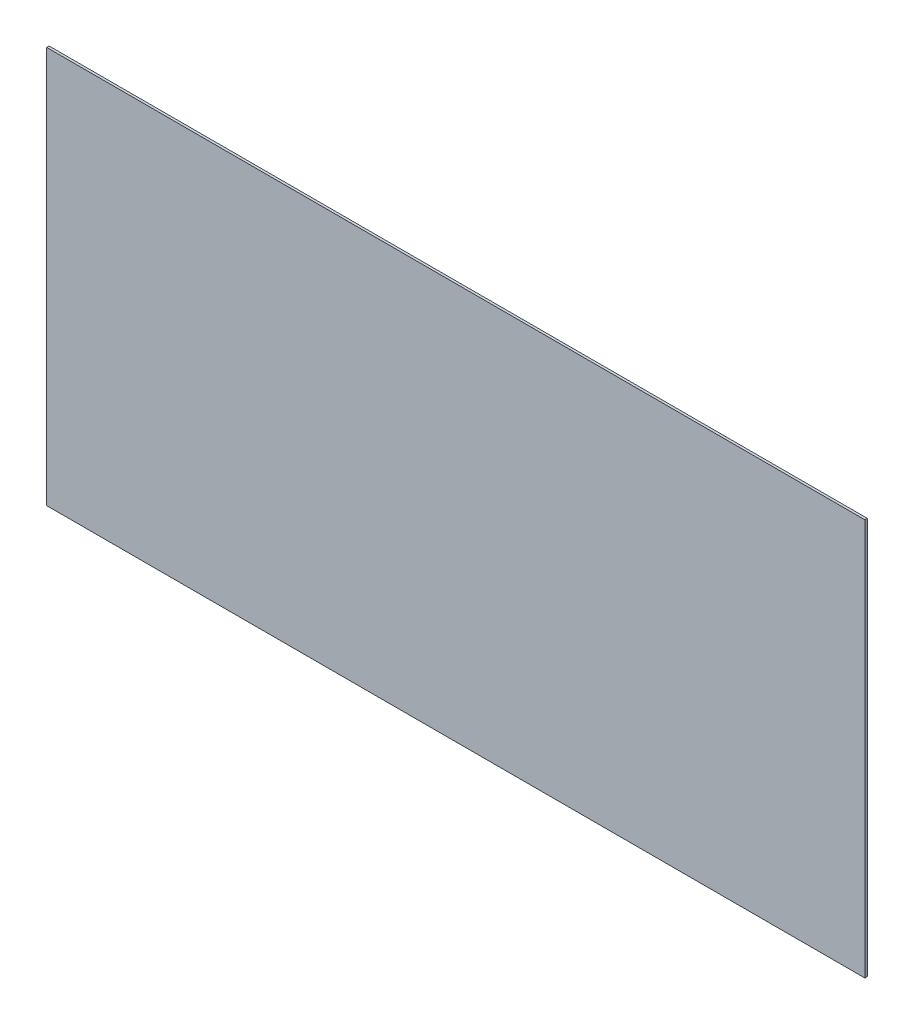
SolidWorks part; units mm, degrees
ref_plane "Plano frontal" through (0, 0, 0) normal (0, 0, 1) x (1, 0, 0)
ref_plane "Plano superior" through (0, 0, 0) normal (0, 1, 0) x (1, 0, 0)
ref_plane "Plano direito" through (0, 0, 0) normal (1, 0, 0) x (0, 0, -1)
sketch "Esboço1" plane through (0, 0, 0) normal (0, 0, 1) x (1, 0, 0)
  line L1 (-25.512, 6.0591) -> (41.488, 6.0591)
  line L2 (-25.512, 6.0591) -> (-25.512, -26.4409)
  line L3 (-25.512, -26.4409) -> (41.488, -26.4409)
  line L4 (41.488, 6.0591) -> (41.488, -26.4409)
  dimension "D1" = 67
  dimension "D2" = 32.5
extrude "Ressalto-extrusão1" add sketch "Esboço1" along normal blind 0.2
